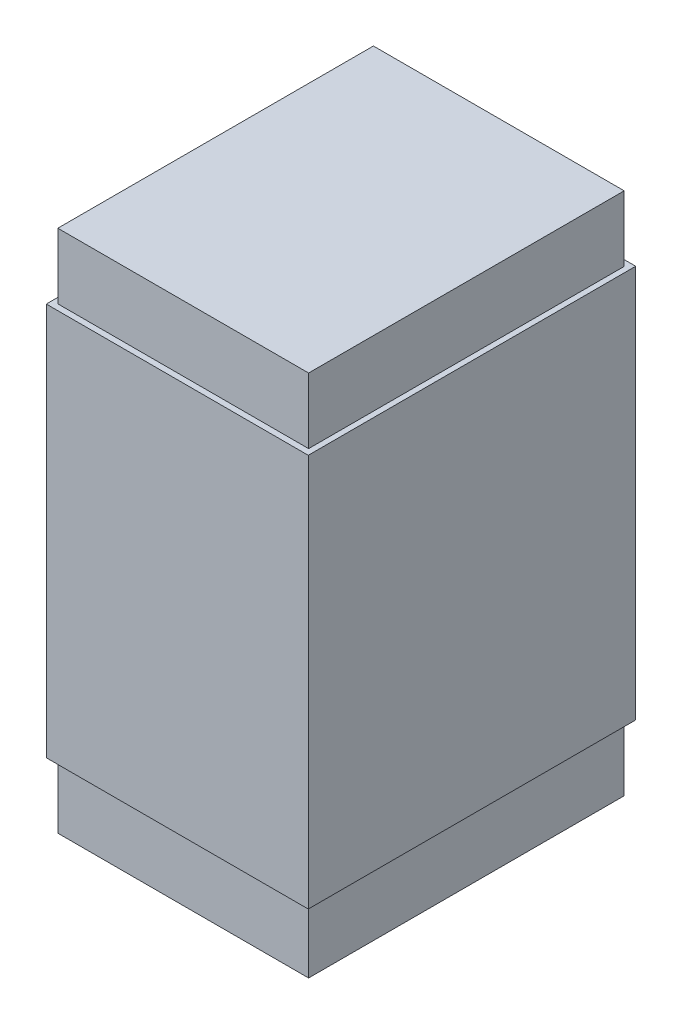
SolidWorks part; units mm, degrees
ref_plane "Front Plane" through (0, 0, 0) normal (0, 0, 1) x (1, 0, 0)
ref_plane "Top Plane" through (0, 0, 0) normal (0, 1, 0) x (1, 0, 0)
ref_plane "Right Plane" through (0, 0, 0) normal (1, 0, 0) x (0, 0, -1)
sketch "Sketch1" plane through (0, 0, 0) normal (0, 1, 0) x (1, 0, 0)
  line L1 (-0.4, -0.5) -> (0.4, -0.5)
  line L2 (-0.4, -0.5) -> (-0.4, 0.5)
  line L3 (-0.4, 0.5) -> (0.4, 0.5)
  line L4 (0.4, -0.5) -> (0.4, 0.5)
  line L5 (-0.4, -0.5) -> (0.4, 0.5) construction
  line L6 (-0.4, 0.5) -> (0.4, -0.5) construction
  point P0 (0, 0)
  dimension "D1" = 1
  dimension "D2" = 0.8
extrude "Boss-Extrude1" add sketch "Sketch1" along normal blind 1.2
sketch "Sketch2" plane through (0, 1.2, 0) normal (0, 1, 0) x (1, 0, 0)
  line L1 (-0.3829, -0.4819) -> (0.3829, -0.4819)
  line L2 (-0.3829, -0.4819) -> (-0.3829, 0.4819)
  line L3 (-0.3829, 0.4819) -> (0.3829, 0.4819)
  line L4 (0.3829, -0.4819) -> (0.3829, 0.4819)
  line L5 (-0.3829, -0.4819) -> (0.3829, 0.4819) construction
  line L6 (-0.3829, 0.4819) -> (0.3829, -0.4819) construction
  point P0 (0, 0)
extrude "Boss-Extrude2" add sketch "Sketch2" along normal blind 0.2
sketch "Sketch3" plane through (0, 0, 0) normal (0, -1, 0) x (1, 0, 0)
  line L8 (-0.3829, -0.4819) -> (0.3829, -0.4819)
  line L9 (-0.3829, 0.4819) -> (-0.3829, -0.4819)
  line L10 (0.3829, -0.4819) -> (0.3829, 0.4819)
  line L11 (0.3829, 0.4819) -> (-0.3829, 0.4819)
  line L12 (-0.3829, -0.4819) -> (0.3829, -0.4819)
  line L13 (-0.3829, 0.4819) -> (-0.3829, -0.4819)
  line L14 (0.3829, -0.4819) -> (0.3829, 0.4819)
  line L15 (0.3829, 0.4819) -> (-0.3829, 0.4819)
  dimension "D1" = 0
extrude "Boss-Extrude3" add sketch "Sketch3" along normal blind 0.2
